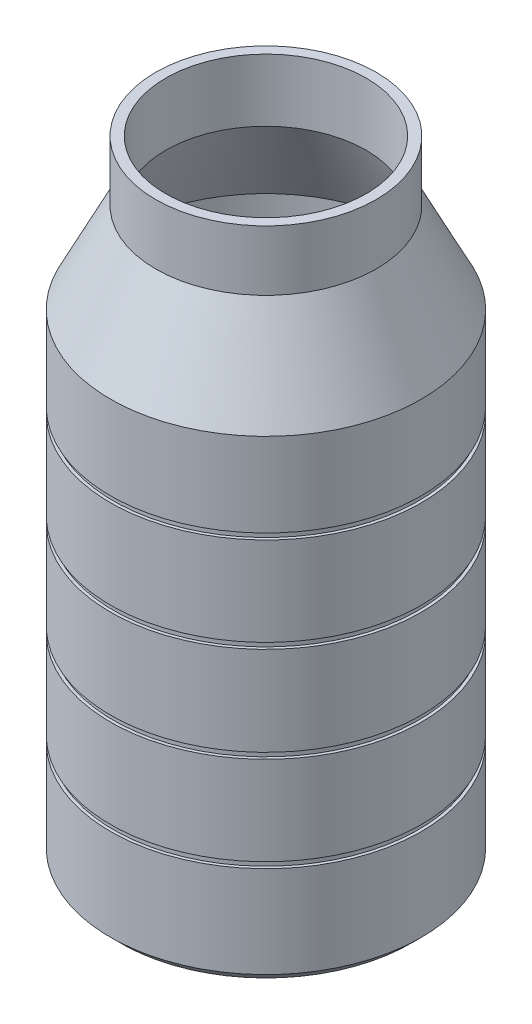
SolidWorks part; units mm, degrees
ref_plane "Front Plane" through (0, 0, 0) normal (0, 0, 1) x (1, 0, 0)
ref_plane "Top Plane" through (0, 0, 0) normal (0, 1, 0) x (1, 0, 0)
ref_plane "Right Plane" through (0, 0, 0) normal (1, 0, 0) x (0, 0, -1)
other "Configuration Table"
sketch "Sketch1" plane through (0, 0, 0) normal (0, 0, 1) x (1, 0, 0)
  line L0 (0, -10) -> (0, 150) construction
  line L1 (0, 0) -> (29, 0)
  line L2 (29, 0) -> (31, 2)
  line L3 (31, 2) -> (31, 20.3)
  line L4 (31, 20.3) -> (30.4, 20.3)
  line L5 (30.4, 20.3) -> (30.4, 21.5)
  line L6 (30.4, 21.5) -> (31, 21.5)
  line L7 (31, 21.5) -> (31, 39.2)
  line L8 (31, 39.2) -> (30.4, 39.2)
  line L9 (30.4, 39.2) -> (30.4, 40.4)
  line L10 (30.4, 40.4) -> (31, 40.4)
  line L11 (31, 40.4) -> (31, 58.2)
  line L12 (31, 58.2) -> (30.4, 58.2)
  line L13 (30.4, 58.2) -> (30.4, 59.4)
  line L14 (30.4, 59.4) -> (31, 59.4)
  line L15 (31, 59.4) -> (31, 77.1)
  line L16 (31, 77.1) -> (30.4, 77.1)
  line L17 (30.4, 77.1) -> (30.4, 78.3)
  line L18 (30.4, 78.3) -> (31, 78.3)
  line L19 (31, 78.3) -> (31, 95)
  line L20 (31, 95) -> (22, 113)
  line L21 (22, 113) -> (22, 125)
  line L22 (22, 125) -> (20, 125)
  line L23 (20, 125) -> (20, 112.53)
  line L24 (20, 112.53) -> (29, 94.53)
  line L25 (29, 94.53) -> (29, 2)
  line L26 (29, 2) -> (0, 2)
  line L27 (0, 2) -> (0, 0)
revolve "Bottle_body_revolve" add sketch "Sketch1" angle 360 about L0
